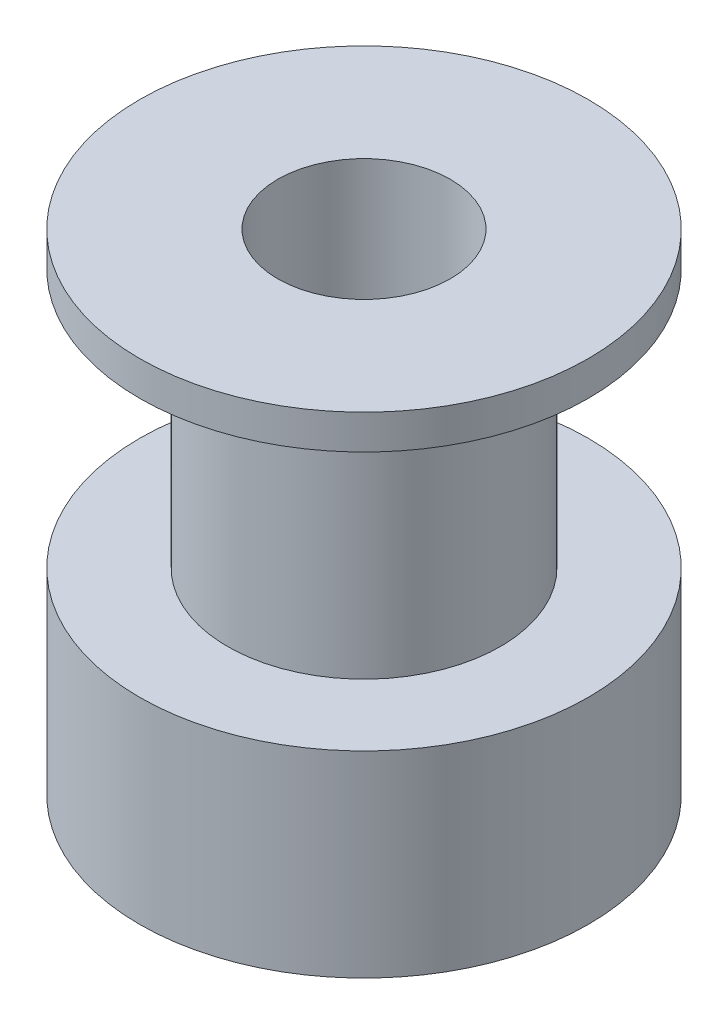
SolidWorks part; units mm, degrees
ref_plane "前视基准面" through (0, 0, 0) normal (0, 0, 1) x (1, 0, 0)
ref_plane "上视基准面" through (0, 0, 0) normal (0, 1, 0) x (1, 0, 0)
ref_plane "右视基准面" through (0, 0, 0) normal (1, 0, 0) x (0, 0, -1)
sketch "草图1" plane through (0, 0, 0) normal (0, 0, 1) x (1, 0, 0)
  line L0 (0, 0) -> (0, 18507.9993) construction
  line L1 (6.5, 15.7832) -> (-6.5, 15.7832)
  line L2 (-6.5, 15.7832) -> (-6.5, 14.7832)
  line L3 (-6.5, 14.7832) -> (-3.9531, 14.7832)
  line L4 (-3.9531, 14.7832) -> (-3.9531, 7.2832)
  line L5 (-3.9531, 7.2832) -> (-6.5, 7.2832)
  line L6 (-6.5, 7.2832) -> (-6.5, 1.5832)
  line L7 (-6.5, 1.5832) -> (6.5, 1.5832)
  line L8 (6.5, 7.2832) -> (6.5, 1.5832)
  line L9 (3.9531, 7.2832) -> (6.5, 7.2832)
  line L10 (3.9531, 14.7832) -> (3.9531, 7.2832)
  line L11 (6.5, 14.7832) -> (3.9531, 14.7832)
  line L12 (6.5, 15.7832) -> (6.5, 14.7832)
  point P12 (0, 1.5832)
  point P17 (0, 15.7832)
  dimension "D1" = 13
  dimension "D2" = 14.2
  dimension "D3" = 7.5
  dimension "D4" = 1
revolve "旋转5" add sketch "草图1" angle 360 about L0
sketch "草图2" plane through (0, 15.7832, 0) normal (0, 1, 0) x (1, 0, 0)
  circle A0 centre (0, 0) radius 2.5
  dimension "D1" = 5
extrude "切除-拉伸1" cut sketch "草图2" against normal through all
